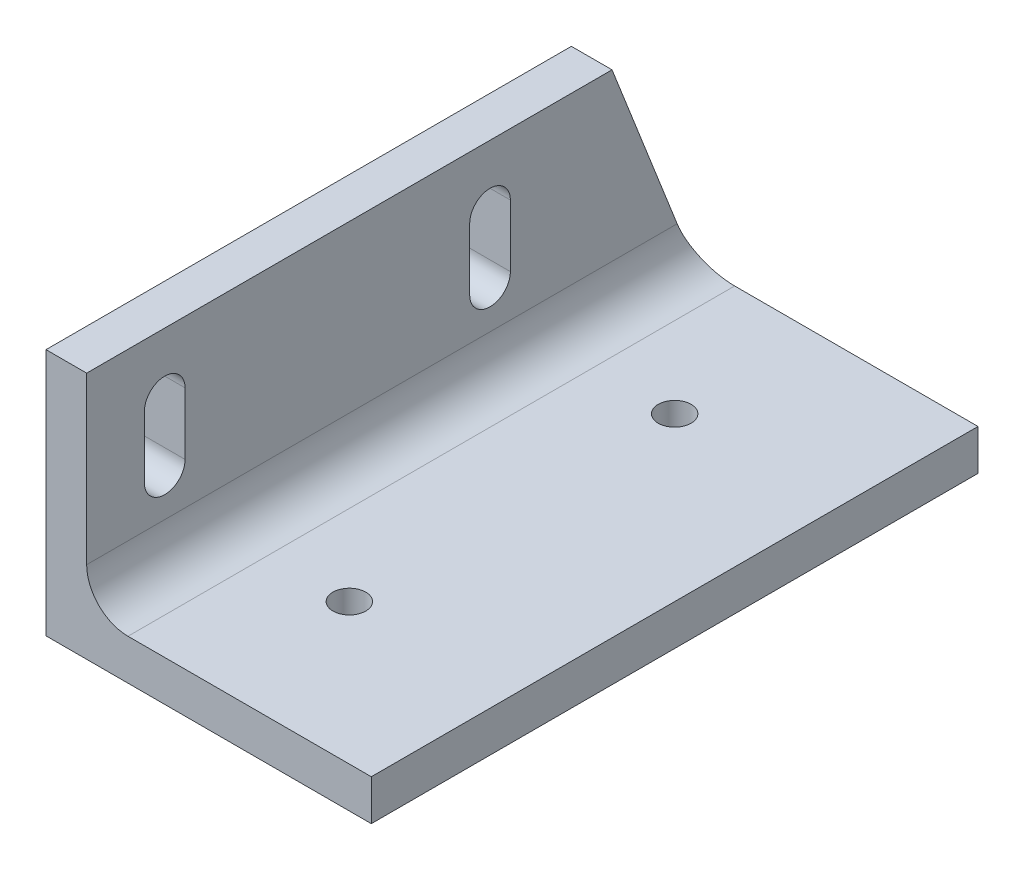
SolidWorks part; units mm, degrees
ref_plane "Front Plane" through (0, 0, 0) normal (0, 0, 1) x (1, 0, 0)
ref_plane "Top Plane" through (0, 0, 0) normal (0, 1, 0) x (1, 0, 0)
ref_plane "Right Plane" through (0, 0, 0) normal (1, 0, 0) x (0, 0, -1)
sketch "Sketch1" plane through (0, 0, 0) normal (0, 0, 1) x (1, 0, 0)
  line L0 (0, 25.48) -> (0, 0)
  line L1 (0, 0) -> (35, 0)
  line L2 (35, 0) -> (35, -5)
  line L3 (35, -5) -> (-5, -5)
  line L4 (-5, -5) -> (-5, 25.48)
  line L5 (-5, 25.48) -> (0, 25.48)
  dimension "D1" = 30.48
extrude "Boss-Extrude1" add sketch "Sketch1" along normal blind 74.6
sketch "Sketch2" plane through (0, 0, 0) normal (0, 1, 0) x (1, 0, 0)
  line L0 (35, -74.6) -> (0, -74.6) construction
  line L2 (-5, -74.6) -> (-5, 0) construction
  circle A0 centre (15, -57.3) radius 0.5
  circle A1 centre (15, -17.3) radius 0.5
  point P5 (17.5, -74.6)
  dimension "D1" = 17.3
  dimension "D4" = 1
  dimension "D2" = 40
  dimension "D3" = 20
sketch "Sketch3" plane through (0, 0, 0) normal (1, 0, 0) x (0, 0, -1)
  line L0 (-65, 10.24) -> (-65, 17.86) construction
  line L1 (-67.5, 10.24) -> (-67.5, 17.86)
  line L2 (-62.5, 10.24) -> (-62.5, 17.86)
  line L3 (-25, 10.24) -> (-25, 17.86) construction
  line L4 (-27.5, 10.24) -> (-27.5, 17.86)
  line L5 (-22.5, 10.24) -> (-22.5, 17.86)
  line L6 (-74.6, -5) -> (0, -5) construction
  line L9 (0, 25.48) -> (0, -5) construction
  arc A0 (-67.5, 10.24) -> (-62.5, 10.24) centre (-65, 10.24) ccw
  arc A1 (-62.5, 17.86) -> (-67.5, 17.86) centre (-65, 17.86) ccw
  arc A2 (-27.5, 10.24) -> (-22.5, 10.24) centre (-25, 10.24) ccw
  arc A3 (-22.5, 17.86) -> (-27.5, 17.86) centre (-25, 17.86) ccw
  point P2 (-65, 14.05)
  point P9 (-25, 14.05)
  dimension "D1" = 15.24
  dimension "D3" = 2.5
  dimension "D2" = 22.86
  dimension "D4" = 25
  dimension "D5" = 40
extrude "Cut-Extrude2" cut sketch "Sketch3" against normal through all
sketch "Sketch4" plane through (0, 0, 0) normal (1, 0, 0) x (0, 0, -1)
  line L0 (0, 0) -> (-10, 25.48)
  line L1 (-74.6, 25.48) -> (0, 25.48) construction
  line L2 (-10, 25.48) -> (0, 25.48)
  line L3 (0, 25.48) -> (0, 0)
  line L4 (-10, 25.48) -> (0, 25.48)
  line L5 (0, 0) -> (0, 25.48)
  line M10 (0, 0) -> (0, 25.48)
  line M11 (0, 25.48) -> (-74.6, 25.48)
extrude "Cut-Extrude3" cut sketch "Sketch4" against normal blind 10 contours L0 M10 M11
fillet "Fillet1" radius 5.08 1 edges at (0, 0, 37.3)
hole_wizard "#10-32 Tapped Hole1" positions "Sketch6" profile "Sketch5" tap size "#10-32" standard "ANSI Inch" end condition through all
sketch "Sketch6" plane through (0, 0, 0) normal (0, 1, 0) x (1, 0, 0)
  point P0 (15, -17.3)
  point P3 (15, -57.3)
cosmetic thread "Hole Thread1" parameters "D2"=4.826
cosmetic thread "Hole Thread2" parameters "D2"=4.826
sketch "Sketch5" plane through (15, 0, 17.3) normal (1, 0, 0) x (0, 0, 1)
  line L0 (0, 0) -> (0, 5)
  line L1 (0, 5) -> (2.0193, 5)
  line L2 (2.0193, 5) -> (2.0193, 0)
  line L5 (2.0193, 0) -> (0, 0)
  line L11 (0, -6.35) -> (0, 107.95) construction
  dimension "Thru Tap Drill Dia." = 4.0386
  dimension "Thru Tap Drill Depth" = 5
